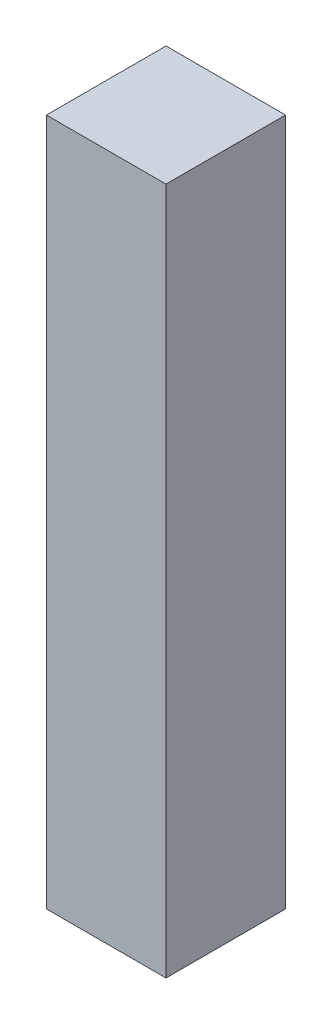
SolidWorks part; units mm, degrees
ref_plane "Front" through (0, 0, 0) normal (0, 0, 1) x (1, 0, 0)
ref_plane "Top" through (0, 0, 0) normal (0, 1, 0) x (1, 0, 0)
ref_plane "Right" through (0, 0, 0) normal (1, 0, 0) x (0, 0, -1)
sketch "Эскиз1" plane through (0, 0, 0) normal (0, 1, 0) x (1, 0, 0)
  line L1 (-487.2474, -647.0304) -> (-447.2474, -647.0304)
  line L2 (-487.2474, -647.0304) -> (-487.2474, -687.0304)
  line L3 (-487.2474, -687.0304) -> (-447.2474, -687.0304)
  line L4 (-447.2474, -647.0304) -> (-447.2474, -687.0304)
  dimension "D1" = 40
  dimension "D2" = 40
extrude "Бобышка-Вытянуть1" add sketch "Эскиз1" along normal blind 230
